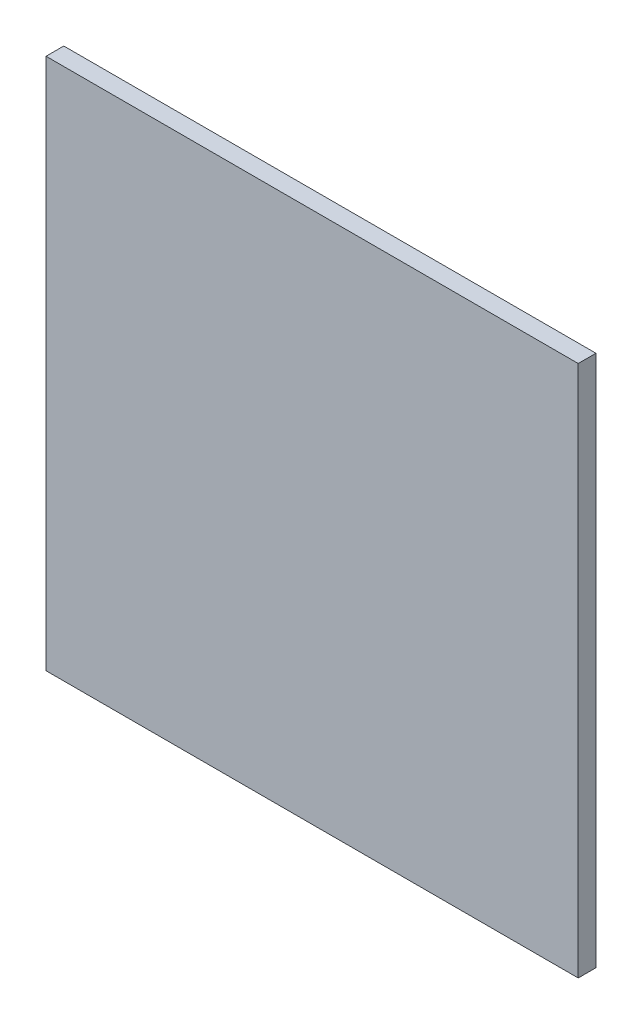
SolidWorks part; units mm, degrees
ref_plane "Front Plane" through (0, 0, 0) normal (0, 0, 1) x (1, 0, 0)
ref_plane "Top Plane" through (0, 0, 0) normal (0, 1, 0) x (1, 0, 0)
ref_plane "Right Plane" through (0, 0, 0) normal (1, 0, 0) x (0, 0, -1)
sketch "Sketch1" plane through (0, 0, 0) normal (0, 0, 1) x (1, 0, 0)
  line L0 (-79.2175, 76.6571) -> (220.7825, 76.6571)
  line L1 (220.7825, 76.6571) -> (220.7825, -223.3429)
  line L2 (220.7825, -223.3429) -> (-79.2175, -223.3429)
  line L3 (-79.2175, -223.3429) -> (-79.2175, 76.6571)
  dimension "D1" = 300
  dimension "D2" = 300
extrude "Boss-Extrude1" add sketch "Sketch1" along normal blind 10
